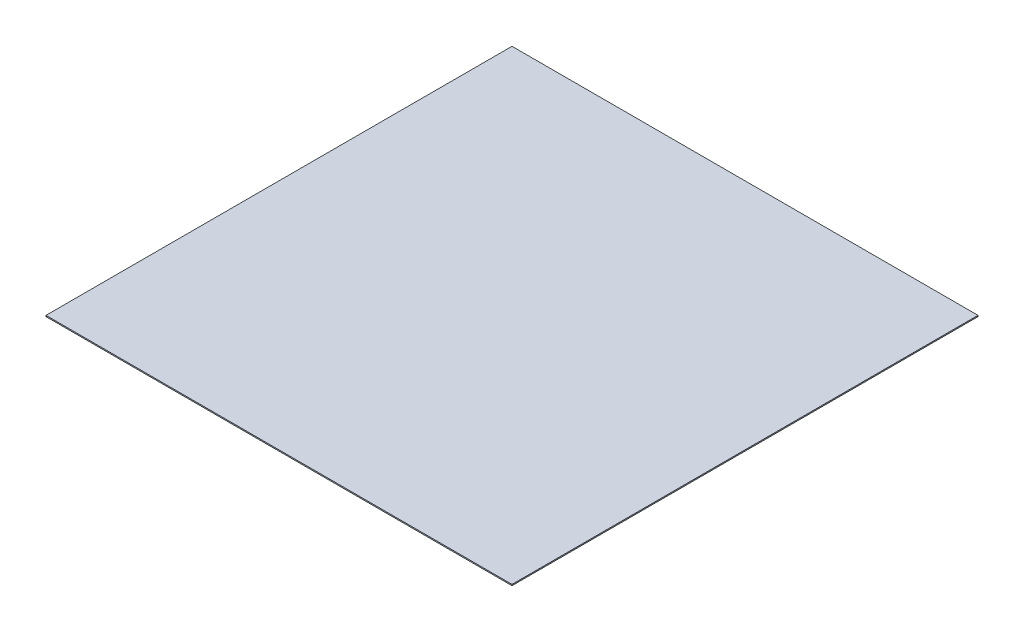
SolidWorks part; units mm, degrees
ref_plane "前视基准面" through (0, 0, 0) normal (0, 0, 1) x (1, 0, 0)
ref_plane "上视基准面" through (0, 0, 0) normal (0, 1, 0) x (1, 0, 0)
ref_plane "右视基准面" through (0, 0, 0) normal (1, 0, 0) x (0, 0, -1)
other "Configuration Table"
sketch "草图1" plane through (0, 0, 0) normal (0, 1, 0) x (1, 0, 0)
  line L1 (200, -200) -> (-200, -200)
  line L2 (200, -200) -> (200, 200)
  line L3 (200, 200) -> (-200, 200)
  line L4 (-200, -200) -> (-200, 200)
  line L5 (200, -200) -> (-200, 200) construction
  line L6 (200, 200) -> (-200, -200) construction
  point P0 (0, 0)
  dimension "D1" = 400
  dimension "D2" = 400
extrude "凸台-拉伸1" add sketch "草图1" along normal blind 1
